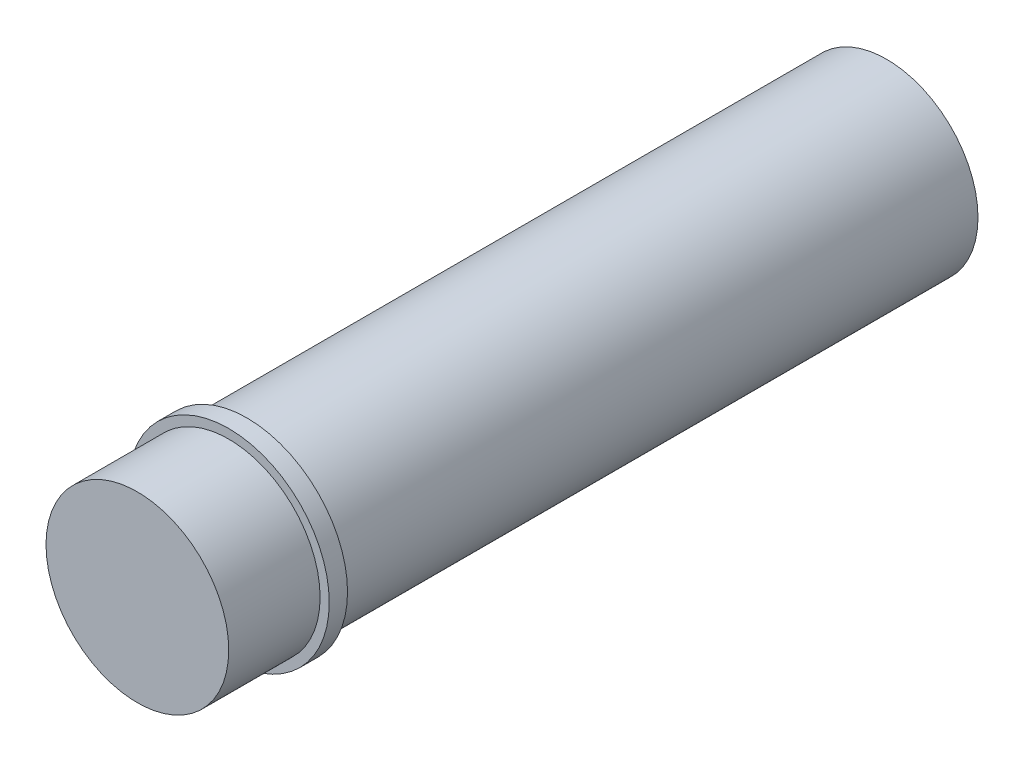
SolidWorks part; units mm, degrees
ref_plane "Front Plane" through (0, 0, 0) normal (0, 0, 1) x (1, 0, 0)
ref_plane "Top Plane" through (0, 0, 0) normal (0, 1, 0) x (1, 0, 0)
ref_plane "Right Plane" through (0, 0, 0) normal (1, 0, 0) x (0, 0, -1)
sketch "Sketch1" plane through (0, 0, 0) normal (0, 0, 1) x (1, 0, 0)
  circle A0 centre (0, 0) radius 12.7
  dimension "D1" = 25.4
extrude "Boss-Extrude1" add sketch "Sketch1" along normal blind 88.9 contours A0
sketch "Sketch2" plane through (0, 0, 88.9) normal (0, 0, 1) x (1, 0, 0)
  circle A0 centre (0, 0) radius 13.97
  dimension "D1" = 27.94
extrude "Boss-Extrude2" add sketch "Sketch2" along normal blind 2.54
sketch "Sketch3" plane through (0, 0, 91.44) normal (0, 0, 1) x (1, 0, 0)
  circle A0 centre (0, 0) radius 12.7
  dimension "D1" = 25.4
extrude "Boss-Extrude3" add sketch "Sketch3" along normal blind 12.7
